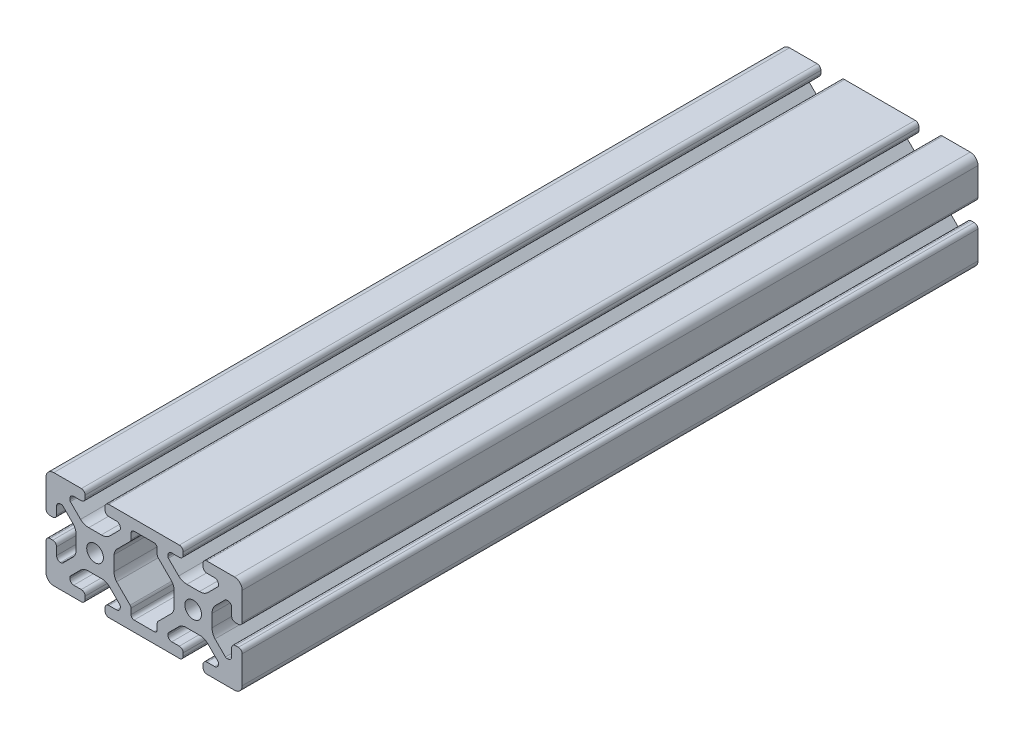
SolidWorks part; units mm, degrees
material "6105-T5 Aluminum"
ref_plane "Front Plane" through (0, 0, 0) normal (0, 0, 1) x (1, 0, 0)
ref_plane "Top Plane" through (0, 0, 0) normal (0, 1, 0) x (1, 0, 0)
ref_plane "Right Plane" through (0, 0, 0) normal (1, 0, 0) x (0, 0, -1)
sketch "Sketch1" plane through (0, 0, 0) normal (0, 0, 1) x (1, 0, 0)
  line L0 (-34.3719, 20) -> (-5.6281, 20)
  line L1 (-35.94, 17.1729) -> (-35.94, 18.3529)
  line L2 (-31.285, 15.68) -> (-34.37, 15.68)
  line L3 (-29.715, 13.6545) -> (-29.715, 14.11)
  line L4 (-15.9282, 15.68) -> (-24.0718, 15.68)
  line L5 (-25.3418, 14.41) -> (-25.3418, 12.1296)
  line L6 (-25.7137, 11.2316) -> (-30.5988, 6.3465)
  line L7 (-32.2841, 3.2591) -> (-32.2841, -2.725)
  line L8 (-14.009, -20) -> (-21.7801, -20)
  line L10 (-24.0718, -15.68) -> (-15.9282, -15.68)
  line L11 (-25.3418, -12.1296) -> (-25.3418, -14.41)
  line L12 (-31.2012, -5.7441) -> (-25.7137, -11.2316)
  line L14 (-29.9376, 13.1171) -> (-34.0919, 8.9628)
  line L15 (-37.4506, 7.7) -> (-42.5494, 7.7)
  line L16 (-45.9081, 8.9628) -> (-50.0624, 13.1171)
  line L17 (-50.285, 13.6545) -> (-50.285, 14.11)
  line L18 (-48.715, 15.68) -> (-45.63, 15.68)
  line L19 (-44.06, 17.25) -> (-44.06, 18.4312)
  line L20 (-45.5696, 20) -> (-53, 20)
  line L21 (-53, 20) -> (-56.83, 20)
  line L22 (-60, 16.8406) -> (-60, 13.0106)
  line L23 (-60, 13.0106) -> (-60, 5.5825)
  line L24 (-58.3243, 4.06) -> (-57.1443, 4.06)
  line L25 (-55.68, 5.6264) -> (-55.68, 8.7114)
  line L26 (-54.11, 10.2814) -> (-53.6509, 10.2814)
  line L27 (-53.1135, 10.0588) -> (-49.0111, 5.9564)
  line L28 (-47.7159, 2.571) -> (-47.7159, -2.502)
  line L29 (-48.9155, -5.8608) -> (-53.1719, -10.1172)
  line L30 (-53.7093, -10.3398) -> (-54.111, -10.3398)
  line L31 (-55.68, -8.715) -> (-55.68, -5.63)
  line L32 (-57.25, -4.06) -> (-58.4312, -4.06)
  line L33 (-60, -5.5696) -> (-60, -13)
  line L34 (-60, -13) -> (-60, -16.83)
  line L35 (-57.0574, -20) -> (-53.2274, -20)
  line L36 (-53.2274, -20) -> (-45.797, -20)
  line L37 (-44.06, -18.4389) -> (-44.06, -17.25)
  line L38 (-45.63, -15.68) -> (-48.715, -15.68)
  line L39 (-50.285, -14.11) -> (-50.285, -13.6545)
  line L40 (-50.0624, -13.1171) -> (-46.3095, -9.3642)
  line L41 (-43.3415, -7.7) -> (-36.6585, -7.7)
  line L42 (-33.6905, -9.3642) -> (-29.9376, -13.1171)
  line L43 (-29.715, -13.6545) -> (-29.715, -14.11)
  line L44 (-31.285, -15.68) -> (-34.37, -15.68)
  line L45 (-35.94, -17.25) -> (-35.94, -18.43)
  line L46 (-34.37, -20) -> (-25.991, -20)
  line L47 (-25.991, -20) -> (-21.7801, -20)
  line L48 (-5.63, -20) -> (-14.009, -20)
  line L49 (-4.06, -17.25) -> (-4.06, -18.43)
  line L50 (-8.715, -15.68) -> (-5.63, -15.68)
  line L51 (-10.285, -13.6545) -> (-10.285, -14.11)
  line L52 (-6.3095, -9.3642) -> (-10.0624, -13.1171)
  line L53 (3.3415, -7.7) -> (-3.3415, -7.7)
  line L54 (10.0624, -13.1171) -> (6.3095, -9.3642)
  line L55 (10.285, -14.11) -> (10.285, -13.6545)
  line L56 (5.63, -15.68) -> (8.715, -15.68)
  line L57 (4.06, -18.4389) -> (4.06, -17.25)
  line L58 (13.2274, -20) -> (5.797, -20)
  line L59 (17.0574, -20) -> (13.2274, -20)
  line L60 (20, -13) -> (20, -16.83)
  line L61 (20, -5.5696) -> (20, -13)
  line L62 (17.25, -4.06) -> (18.4312, -4.06)
  line L63 (15.68, -8.715) -> (15.68, -5.63)
  line L64 (13.7093, -10.3398) -> (14.111, -10.3398)
  line L65 (8.9155, -5.8608) -> (13.1719, -10.1172)
  line L66 (7.7159, 2.571) -> (7.7159, -2.502)
  line L67 (13.1135, 10.0588) -> (9.0111, 5.9564)
  line L68 (14.11, 10.2814) -> (13.6509, 10.2814)
  line L69 (15.68, 5.6264) -> (15.68, 8.7114)
  line L70 (18.3243, 4.06) -> (17.1443, 4.06)
  line L71 (20, 13.0106) -> (20, 5.5825)
  line L72 (20, 16.8406) -> (20, 13.0106)
  line L73 (13, 20) -> (16.83, 20)
  line L74 (5.5696, 20) -> (13, 20)
  line L75 (4.06, 17.25) -> (4.06, 18.4312)
  line L76 (8.715, 15.68) -> (5.63, 15.68)
  line L77 (10.285, 13.6545) -> (10.285, 14.11)
  line L78 (5.9081, 8.9628) -> (10.0624, 13.1171)
  line L79 (-2.5494, 7.7) -> (2.5494, 7.7)
  line L80 (-10.0624, 13.1171) -> (-5.9081, 8.9628)
  line L81 (-8.7988, -5.7441) -> (-14.2863, -11.2316)
  line L82 (-14.6582, -12.1296) -> (-14.6582, -14.41)
  line L83 (-7.7159, 3.2591) -> (-7.7159, -2.725)
  line L84 (-14.2863, 11.2316) -> (-9.4012, 6.3465)
  line L85 (-14.6582, 14.41) -> (-14.6582, 12.1296)
  line L86 (-10.285, 13.6545) -> (-10.285, 14.11)
  line L87 (-8.715, 15.68) -> (-5.63, 15.68)
  line L88 (-4.06, 17.1729) -> (-4.06, 18.3529)
  line L89 (-40, 24.8708) -> (-40, -18.43) construction
  line L91 (-23.0962, 16.9038) -> (-63.6857, -23.6857) construction
  line L92 (-56.2671, 16.2671) -> (-22.7875, -17.2125) construction
  arc A0 (-35.94, 18.3529) -> (-34.3719, 20) centre (-34.3719, 18.43) cw
  circle A1 centre (-40, 0) radius 3.4
  arc A2 (-34.37, 15.68) -> (-35.94, 17.1729) centre (-34.3719, 17.25) cw
  arc A3 (-31.285, 15.68) -> (-29.715, 14.11) centre (-31.285, 14.11) cw
  arc A4 (-29.715, 13.6545) -> (-29.9376, 13.1171) centre (-30.475, 13.6545) cw
  arc A5 (-32.2841, -2.725) -> (-31.2012, -5.7441) centre (-27.5341, -2.725) ccw
  arc A6 (-24.0718, 15.68) -> (-25.3418, 14.41) centre (-24.0718, 14.41) ccw
  arc A7 (-25.7137, 11.2316) -> (-25.3418, 12.1296) centre (-26.6118, 12.1296) ccw
  arc A8 (-30.5988, 6.3465) -> (-32.2841, 3.2591) centre (-27.5685, 2.6887) ccw
  arc A9 (-25.3418, -14.41) -> (-24.0718, -15.68) centre (-24.0718, -14.41) ccw
  arc A10 (-25.3418, -12.1296) -> (-25.7137, -11.2316) centre (-26.6118, -12.1296) ccw
  arc A11 (-37.4506, 7.7) -> (-34.0919, 8.9628) centre (-37.3191, 12.4482) ccw
  arc A12 (-45.9081, 8.9628) -> (-42.5494, 7.7) centre (-42.6809, 12.4482) ccw
  arc A13 (-50.285, 13.6545) -> (-50.0624, 13.1171) centre (-49.525, 13.6545) ccw
  arc A14 (-48.715, 15.68) -> (-50.285, 14.11) centre (-48.715, 14.11) ccw
  arc A15 (-45.63, 15.68) -> (-44.06, 17.25) centre (-45.63, 17.25) ccw
  arc A16 (-44.06, 18.4312) -> (-45.5696, 20) centre (-45.63, 18.4312) ccw
  arc A17 (-56.83, 20) -> (-60, 16.8406) centre (-56.83, 16.83) ccw
  arc A18 (-60, 5.5825) -> (-58.3243, 4.06) centre (-58.4306, 5.6264) ccw
  arc A19 (-57.1443, 4.06) -> (-55.68, 5.6264) centre (-57.25, 5.6264) ccw
  arc A20 (-54.11, 10.2814) -> (-55.68, 8.7114) centre (-54.11, 8.7114) ccw
  arc A21 (-53.1135, 10.0588) -> (-53.6509, 10.2814) centre (-53.6509, 9.5214) ccw
  arc A22 (-47.7159, 2.571) -> (-49.0111, 5.9564) centre (-52.4643, 2.6948) ccw
  arc A23 (-48.9155, -5.8608) -> (-47.7159, -2.502) centre (-52.4617, -2.7006) ccw
  arc A24 (-53.7093, -10.3398) -> (-53.1719, -10.1172) centre (-53.7093, -9.5798) ccw
  arc A25 (-55.68, -8.715) -> (-54.111, -10.3398) centre (-54.111, -8.7698) ccw
  arc A26 (-55.68, -5.63) -> (-57.25, -4.06) centre (-57.25, -5.63) ccw
  arc A27 (-58.4312, -4.06) -> (-60, -5.5696) centre (-58.4312, -5.63) ccw
  arc A28 (-60, -16.83) -> (-57.0574, -20) centre (-56.83, -16.8382) ccw
  arc A29 (-45.797, -20) -> (-44.06, -18.4389) centre (-45.63, -18.4389) ccw
  arc A30 (-44.06, -17.25) -> (-45.63, -15.68) centre (-45.63, -17.25) ccw
  arc A31 (-50.285, -14.11) -> (-48.715, -15.68) centre (-48.715, -14.11) ccw
  arc A32 (-50.0624, -13.1171) -> (-50.285, -13.6545) centre (-49.525, -13.6545) ccw
  arc A33 (-43.3415, -7.7) -> (-46.3095, -9.3642) centre (-42.6565, -12.4003) ccw
  arc A34 (-33.6905, -9.3642) -> (-36.6585, -7.7) centre (-37.3435, -12.4003) ccw
  arc A35 (-29.715, -13.6545) -> (-29.9376, -13.1171) centre (-30.475, -13.6545) ccw
  arc A36 (-31.285, -15.68) -> (-29.715, -14.11) centre (-31.285, -14.11) ccw
  arc A37 (-34.37, -15.68) -> (-35.94, -17.25) centre (-34.37, -17.25) ccw
  arc A38 (-35.94, -18.43) -> (-34.37, -20) centre (-34.37, -18.43) ccw
  arc A39 (-4.06, -18.43) -> (-5.63, -20) centre (-5.63, -18.43) cw
  arc A40 (-5.63, -15.68) -> (-4.06, -17.25) centre (-5.63, -17.25) cw
  arc A41 (-8.715, -15.68) -> (-10.285, -14.11) centre (-8.715, -14.11) cw
  arc A42 (-10.285, -13.6545) -> (-10.0624, -13.1171) centre (-9.525, -13.6545) cw
  arc A43 (-6.3095, -9.3642) -> (-3.3415, -7.7) centre (-2.6565, -12.4003) cw
  arc A44 (3.3415, -7.7) -> (6.3095, -9.3642) centre (2.6565, -12.4003) cw
  arc A45 (10.0624, -13.1171) -> (10.285, -13.6545) centre (9.525, -13.6545) cw
  arc A46 (10.285, -14.11) -> (8.715, -15.68) centre (8.715, -14.11) cw
  arc A47 (4.06, -17.25) -> (5.63, -15.68) centre (5.63, -17.25) cw
  arc A48 (5.797, -20) -> (4.06, -18.4389) centre (5.63, -18.4389) cw
  arc A49 (20, -16.83) -> (17.0574, -20) centre (16.83, -16.8382) cw
  arc A50 (18.4312, -4.06) -> (20, -5.5696) centre (18.4312, -5.63) cw
  arc A51 (15.68, -5.63) -> (17.25, -4.06) centre (17.25, -5.63) cw
  arc A52 (15.68, -8.715) -> (14.111, -10.3398) centre (14.111, -8.7698) cw
  arc A53 (13.7093, -10.3398) -> (13.1719, -10.1172) centre (13.7093, -9.5798) cw
  arc A54 (8.9155, -5.8608) -> (7.7159, -2.502) centre (12.4617, -2.7006) cw
  arc A55 (7.7159, 2.571) -> (9.0111, 5.9564) centre (12.4643, 2.6948) cw
  arc A56 (13.1135, 10.0588) -> (13.6509, 10.2814) centre (13.6509, 9.5214) cw
  arc A57 (14.11, 10.2814) -> (15.68, 8.7114) centre (14.11, 8.7114) cw
  arc A58 (17.1443, 4.06) -> (15.68, 5.6264) centre (17.25, 5.6264) cw
  arc A59 (20, 5.5825) -> (18.3243, 4.06) centre (18.4306, 5.6264) cw
  arc A60 (16.83, 20) -> (20, 16.8406) centre (16.83, 16.83) cw
  arc A61 (4.06, 18.4312) -> (5.5696, 20) centre (5.63, 18.4312) cw
  arc A62 (5.63, 15.68) -> (4.06, 17.25) centre (5.63, 17.25) cw
  arc A63 (8.715, 15.68) -> (10.285, 14.11) centre (8.715, 14.11) cw
  arc A64 (10.285, 13.6545) -> (10.0624, 13.1171) centre (9.525, 13.6545) cw
  arc A65 (5.9081, 8.9628) -> (2.5494, 7.7) centre (2.6809, 12.4482) cw
  arc A66 (-2.5494, 7.7) -> (-5.9081, 8.9628) centre (-2.6809, 12.4482) cw
  arc A67 (-14.6582, -12.1296) -> (-14.2863, -11.2316) centre (-13.3882, -12.1296) cw
  arc A68 (-14.6582, -14.41) -> (-15.9282, -15.68) centre (-15.9282, -14.41) cw
  arc A69 (-9.4012, 6.3465) -> (-7.7159, 3.2591) centre (-12.4315, 2.6887) cw
  arc A70 (-14.2863, 11.2316) -> (-14.6582, 12.1296) centre (-13.3882, 12.1296) cw
  arc A71 (-15.9282, 15.68) -> (-14.6582, 14.41) centre (-15.9282, 14.41) cw
  arc A72 (-7.7159, -2.725) -> (-8.7988, -5.7441) centre (-12.4659, -2.725) cw
  arc A73 (-10.285, 13.6545) -> (-10.0624, 13.1171) centre (-9.525, 13.6545) ccw
  arc A74 (-8.715, 15.68) -> (-10.285, 14.11) centre (-8.715, 14.11) ccw
  arc A75 (-5.63, 15.68) -> (-4.06, 17.1729) centre (-5.6281, 17.25) ccw
  circle A76 centre (0, 0) radius 3.4
  arc A77 (-4.06, 18.3529) -> (-5.6281, 20) centre (-5.6281, 18.43) ccw
  dimension "D4" = 6.8
  dimension "D1" = 80
  dimension "D2" = 40
  dimension "D3" = 20
  dimension "D5" = 8.12
  dimension "D6" = 4.32
  dimension "D7" = 20.57
  dimension "D8" = 4.32
  dimension "D9" = 8.12
  dimension "D10" = 12.3
  dimension "D11" = 4.32
  dimension "D12" = 4.32
  dimension "D13" = 4.32
extrude "Extrude1" add sketch "Sketch1" against normal blind 300
